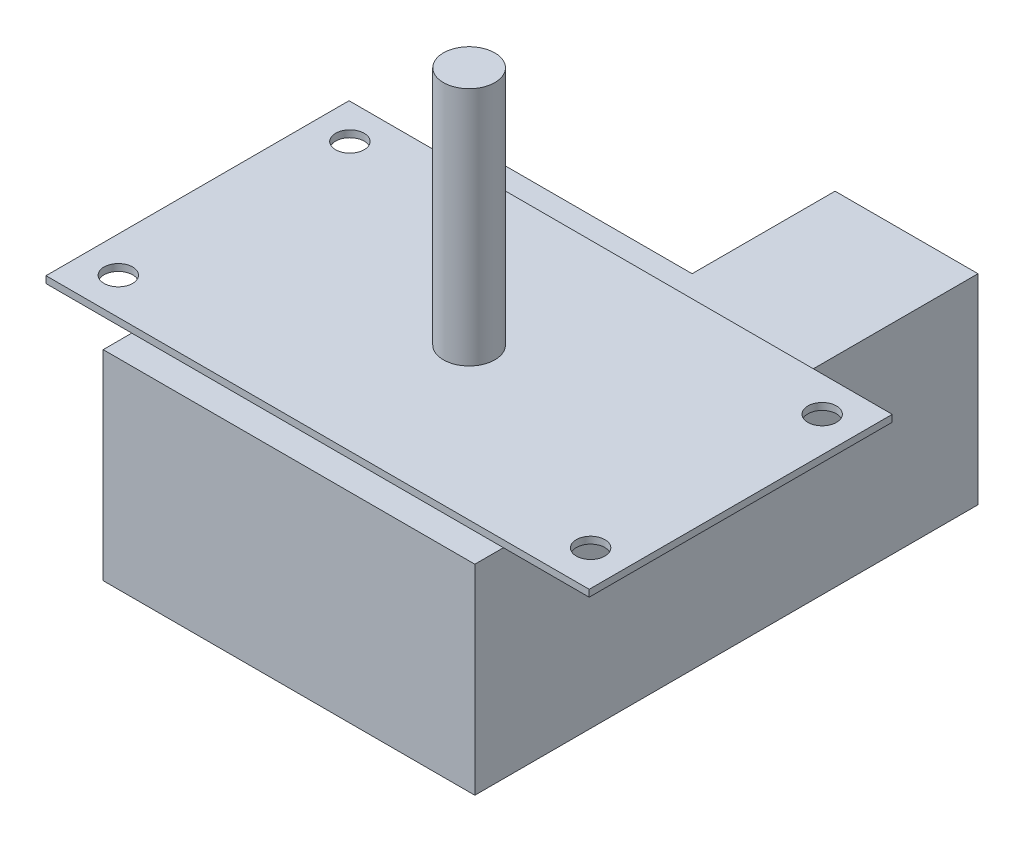
SolidWorks part; units mm, degrees
ref_plane "前视基准面" through (0, 0, 0) normal (0, 0, 1) x (1, 0, 0)
ref_plane "上视基准面" through (0, 0, 0) normal (0, 1, 0) x (1, 0, 0)
ref_plane "右视基准面" through (0, 0, 0) normal (1, 0, 0) x (0, 0, -1)
sketch "草图1" plane through (0, 0, 0) normal (0, 1, 0) x (1, 0, 0)
  line L1 (-47.5, -26.5) -> (47.5, -26.5)
  line L2 (-47.5, -26.5) -> (-47.5, 26.5)
  line L3 (-47.5, 26.5) -> (47.5, 26.5)
  line L4 (47.5, -26.5) -> (47.5, 26.5)
  line L5 (-47.5, -26.5) -> (47.5, 26.5) construction
  line L6 (-47.5, 26.5) -> (47.5, -26.5) construction
  text T0 "右上"
  point P0 (0, 0)
  dimension "D1" = 53
  dimension "D2" = 95
extrude "盖板" add sketch "草图1" along normal blind 1.2 contours L2 L1 L4 L3
sketch "草图5" plane through (0, 1.2, 0) normal (0, 1, 0) x (1, 0, 0)
  line L0 (47.5, 26.5) -> (47.5, 20.4) construction
  line L1 (47.5, -26.5) -> (47.5, 26.5) construction
  line L2 (47.5, 20.4) -> (41.35, 20.4) construction
  line L3 (-47.5, 26.5) -> (-47.5, 20.4) construction
  line L4 (-47.5, -26.5) -> (-47.5, 26.5) construction
  line L5 (-47.5, 20.4) -> (-41.25, 20.4) construction
  line L6 (47.5, -26.5) -> (47.5, -20.1) construction
  line L7 (47.5, -20.1) -> (41.35, -20.1) construction
  line L8 (-47.5, -26.5) -> (-47.5, -20.1) construction
  line L9 (-47.5, -20.1) -> (-41.25, -20.1) construction
  circle A0 centre (-41.25, 20.4) radius 2.5
  circle A1 centre (41.35, 20.4) radius 2.5
  circle A2 centre (-41.25, -20.1) radius 2.5
  circle A3 centre (41.35, -20.1) radius 2.5
  dimension "D1" = 6.1
  dimension "D2" = 6.15
  dimension "D3" = 6.1
  dimension "D4" = 6.25
  dimension "D5" = 6.4
  dimension "D6" = 6.15
  dimension "D7" = 6.4
  dimension "D8" = 6.25
extrude "螺丝" cut sketch "草图5" against normal up to next
sketch "草图6" plane through (0, 0, 0) normal (0, -1, 0) x (1, 0, 0)
  line L0 (47.5, -26.5) -> (32.5, -26.5) construction
  line L1 (-47.5, -26.5) -> (47.5, -26.5) construction
  line L2 (32.5, -26.5) -> (32.5, -56.5) construction
  line L3 (32.5, -56.5) -> (7.5, -56.5) construction
  line L4 (7.5, -26.5) -> (7.5, -31.5) construction
  line L5 (-47.5, -31.5) -> (-32.5, -31.5) construction
  line L6 (-32.5, 26.5) -> (-32.5, 31.5) construction
  line L7 (-47.5, 26.5) -> (47.5, 26.5) construction
  line L8 (32.5, -26.5) -> (32.5, 31.5) construction
  line L9 (32.5, 31.5) -> (-32.5, 31.5) construction
  line L10 (32.5, -56.5) -> (7.5, -56.5)
  line L27 (7.5, -56.5) -> (7.5, -31.5)
  line L28 (7.5, -31.5) -> (-32.5, -31.5)
  line L29 (-32.5, -31.5) -> (-32.5, 31.5)
  line L30 (-32.5, 31.5) -> (32.5, 31.5)
  line L31 (32.5, 31.5) -> (32.5, -56.5)
  dimension "D1" = 15
  dimension "D2" = 30
  dimension "D3" = 25
  dimension "D4" = 5
  dimension "D5" = 15
  dimension "D6" = 5
extrude "结构" add sketch "草图6" along normal blind 35
sketch "草图7" plane through (0, 1.2, 0) normal (0, 1, 0) x (1, 0, 0)
  circle A0 centre (0, 0) radius 4.5
extrude "摇杆" add sketch "草图7" along normal blind 42
